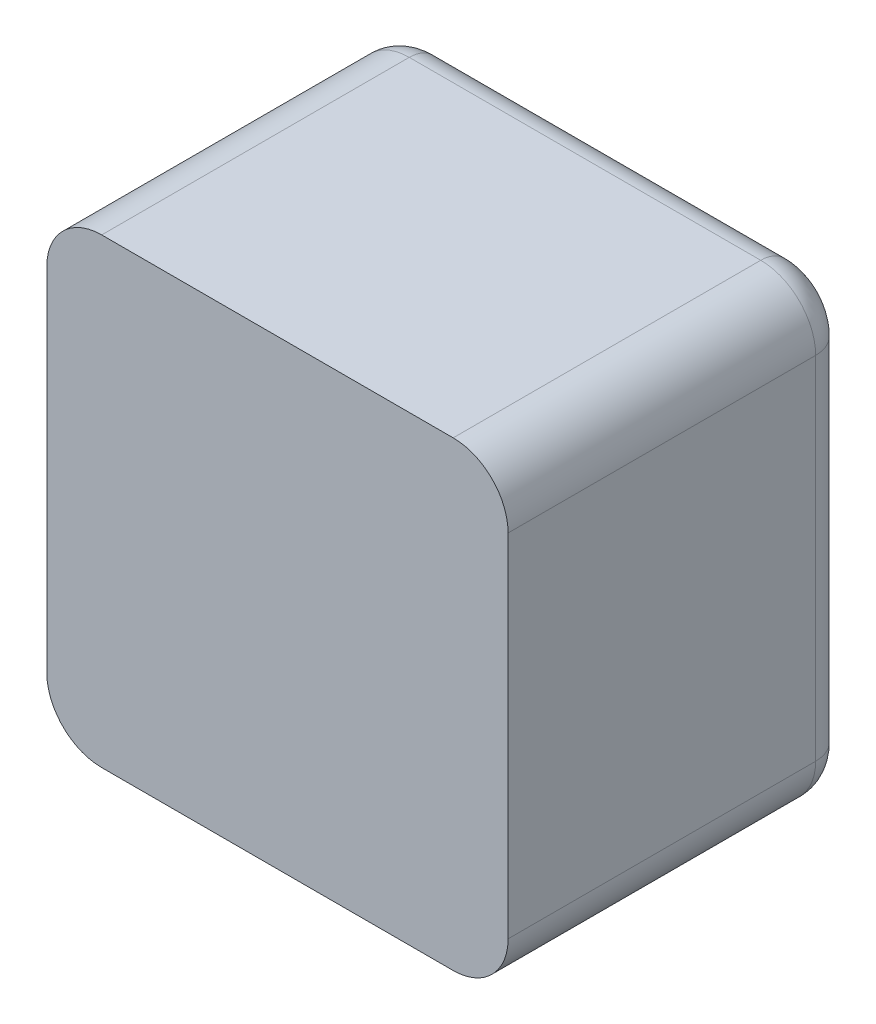
SolidWorks part; units mm, degrees
ref_plane "Plan de face" through (0, 0, 0) normal (0, 0, 1) x (1, 0, 0)
ref_plane "Plan de dessus" through (0, 0, 0) normal (0, 1, 0) x (1, 0, 0)
ref_plane "Plan de droite" through (0, 0, 0) normal (1, 0, 0) x (0, 0, -1)
sketch "Esquisse1" plane through (0, 0, 0) normal (0, 0, 1) x (1, 0, 0)
  line L1 (-29.6482, 56.1094) -> (54.3518, 56.1094)
  line L2 (-29.6482, 56.1094) -> (-29.6482, -27.8906)
  line L3 (-29.6482, -27.8906) -> (54.3518, -27.8906)
  line L4 (54.3518, 56.1094) -> (54.3518, -27.8906)
  dimension "D1" = 84
  dimension "D2" = 84
extrude "Boss.-Extru.1" add sketch "Esquisse1" along normal blind 60 contours L1 L4 L3 L2
fillet "Congé1" radius 10 4 edges at (-29.6482, -27.8906, 30) (54.3518, -27.8906, 30) (-29.6482, 56.1094, 30) (54.3518, 56.1094, 30)
fillet "Congé2" radius 6 8 edges at (-26.7193, 53.1804, 0) (-29.6482, 14.1094, 0) (-26.7193, -24.9617, 0) (12.3518, -27.8906, 0) (51.4229, -24.9617, 0) (54.3518, 14.1094, 0) (51.4229, 53.1804, 0) (12.3518, 56.1094, 0)
sketch "Esquisse2" plane through (0, -27.8906, 0) normal (0, -1, 0) x (1, 0, 0)
  line L0 (-19.6482, 60) -> (44.3518, 60) construction
  line L1 (24.3518, 57) -> (0.3518, 57)
  line L2 (39.3518, 42) -> (39.3518, 25)
  line L3 (24.3518, 10) -> (0.3518, 10)
  line L4 (-14.6482, 42) -> (-14.6482, 25)
  line L5 (-29.6482, 6) -> (-29.6482, 60) construction
  circle A0 centre (12.3518, 34) radius 3.175
  arc A1 (0.3518, 57) -> (-14.6482, 42) centre (0.3518, 42) ccw
  arc A2 (0.3518, 10) -> (-14.6482, 25) centre (0.3518, 25) cw
  arc A3 (39.3518, 25) -> (24.3518, 10) centre (24.3518, 25) cw
  arc A4 (24.3518, 57) -> (39.3518, 42) centre (24.3518, 42) cw
  point P10 (0, 0)
  point P13 (-14.6482, 57)
  point P16 (-14.6482, 10)
  point P19 (39.3518, 10)
  dimension "D5" = 6.35
  dimension "D8" = 15
  dimension "D1" = 54
  dimension "D2" = 47
  dimension "D3" = 3
  dimension "D4" = 15
  dimension "D6" = 23
  dimension "D7" = 27
extrude "Boss.-Extru.2" add sketch "Esquisse2" along normal blind 2 contours A4 L2 A3 L3 A2 L4 A1 L1
sketch "Esquisse5" plane through (0, -29.8906, 0) normal (0, -1, 0) x (1, 0, 0)
  line L0 (24.3518, 57) -> (0.3518, 57) construction
  line L1 (-14.6482, 42) -> (-14.6482, 25) construction
  circle A0 centre (12.3518, 34) radius 3.175
  dimension "D1" = 6.35
  dimension "D2" = 23
  dimension "D3" = 27
extrude "Enlèv. mat.-Extru.1" cut sketch "Esquisse5" against normal blind 6
sketch "Esquisse6" plane through (0, 0, 0) normal (0, 0, -1) x (-1, 0, 0)
  line L0 (-34.8518, -8.3906) -> (10.1482, -8.3906) construction
  line L1 (-34.8518, -1.8906) -> (10.1482, -1.8906)
  line L2 (-34.8518, -14.8906) -> (10.1482, -14.8906)
  line L7 (-54.3518, -17.8906) -> (-54.3518, 46.1094) construction
  line L8 (19.6482, -27.8906) -> (-44.3518, -27.8906) construction
  arc A0 (-34.8518, -1.8906) -> (-34.8518, -14.8906) centre (-34.8518, -8.3906) ccw
  arc A1 (10.1482, -14.8906) -> (10.1482, -1.8906) centre (10.1482, -8.3906) ccw
  point P2 (-12.3518, -8.3906)
  dimension "D1" = 13
  dimension "D2" = 45
  dimension "D3" = 42
  dimension "D4" = 13
extrude "Enlèv. mat.-Extru.2" cut sketch "Esquisse6" against normal blind 9 contours L1 A1 L2 A0
sketch "Esquisse7" plane through (0, 0, 0) normal (0, 0, -1) x (-1, 0, 0)
  line L0 (-54.3518, -17.8906) -> (-54.3518, 46.1094) construction
  line L1 (-44.3518, 56.1094) -> (19.6482, 56.1094) construction
  circle A0 centre (-14.3518, 21.1094) radius 3.175
  dimension "D1" = 6.35
  dimension "D2" = 40
  dimension "D3" = 35
extrude "Enlèv. mat.-Extru.3" cut sketch "Esquisse7" against normal blind 6
sketch "Esquisse8" plane through (0, 0, 60) normal (0, 0, 1) x (1, 0, 0)
  line L0 (54.3518, 46.1094) -> (54.3518, -17.8906) construction
  line L1 (-19.6482, 56.1094) -> (44.3518, 56.1094)
  line L2 (-29.6482, 46.1094) -> (-29.6482, -17.8906)
  line L3 (-19.6482, -27.8906) -> (44.3518, -27.8906)
  line L4 (54.3518, 46.1094) -> (54.3518, -17.8906)
  line L5 (-29.6482, 46.1094) -> (-29.6482, -17.8906) construction
  line L6 (-19.6482, -27.8906) -> (44.3518, -27.8906) construction
  line L7 (-19.6482, 56.1094) -> (44.3518, 56.1094) construction
  arc A0 (-29.6482, -17.8906) -> (-19.6482, -27.8906) centre (-19.6482, -17.8906) ccw
  arc A1 (44.3518, -27.8906) -> (54.3518, -17.8906) centre (44.3518, -17.8906) ccw
  arc A2 (44.3518, 56.1094) -> (54.3518, 46.1094) centre (44.3518, 46.1094) cw
  arc A3 (-19.6482, 56.1094) -> (-29.6482, 46.1094) centre (-19.6482, 46.1094) ccw
  dimension "D1" = 10
extrude "Boss.-Extru.3" add sketch "Esquisse8" along normal blind 2
